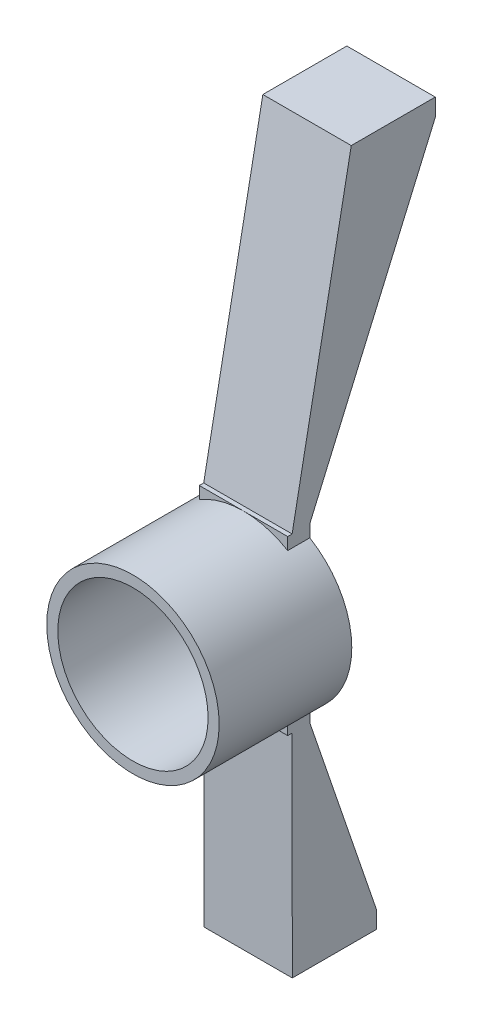
SolidWorks part; units mm, degrees
ref_plane "Front Plane" through (0, 0, 0) normal (0, 0, 1) x (1, 0, 0)
ref_plane "Top Plane" through (0, 0, 0) normal (0, 1, 0) x (1, 0, 0)
ref_plane "Right Plane" through (0, 0, 0) normal (1, 0, 0) x (0, 0, -1)
sketch "Sketch2" plane through (0, 0, 0) normal (0, 0, 1) x (1, 0, 0)
  circle A0 centre (0, 0) radius 39
  circle A1 centre (0, 0) radius 34
  dimension "D1" = 78
  dimension "D2" = 5
extrude "Boss-Extrude1" add sketch "Sketch2" along normal blind 60
ref_plane "Plane1" through (0, 0, 0) normal (1, 0, 0) x (0, 0, -1)
sketch "Sketch4" plane through (0, 0, 0) normal (1, 0, 0) x (0, 0, -1)
  line L0 (-60, 39) -> (0, 39) construction
  line L1 (0, 39) -> (0, -39) construction
  line L2 (0, -39) -> (-60, -39) construction
  line L3 (-60, -39) -> (-60, 39) construction
  line L4 (0, 39) -> (36.6421, 39) construction
  line L5 (0, 39) -> (29.2171, 190.5797) construction
  line L6 (-8, 39) -> (21.1116, 190.0326) construction
  line L7 (-8, 39) -> (18.7538, 177.8)
  line L8 (18.7538, 177.8) -> (56.7538, 177.8)
  line L9 (0, 39) -> (25.2118, 169.8)
  line L10 (25.2118, 169.8) -> (56.7538, 169.8)
  line L11 (56.7538, 169.8) -> (56.7538, 177.8)
  line L12 (0, 39) -> (-8, 39)
  point P8 (-8, 39)
  point P13 (18.7538, 177.8)
  point P14 (25.2118, 169.8)
  dimension "D1" = 8
  dimension "D2" = 79.09
  dimension "D3" = 100.91
  dimension "D4" = 138.8
  dimension "D5" = 130.8
  dimension "D6" = 38
extrude "Boss-Extrude2" add sketch "Sketch4" along normal mid plane 40 separate body
sketch "Sketch5" plane through (0, 0, 0) normal (0, 0, -1) x (-1, 0, 0)
  line L0 (-20, 39) -> (-20, 33.4813)
  line L1 (20, 39) -> (20, 33.4813)
  line L4 (20, 39) -> (20, 169.8)
  line L5 (20, 169.8) -> (-20, 169.8)
  line L6 (-20, 169.8) -> (-20, 39)
  line L7 (-20, 39) -> (20, 39)
  line L11 (-20, 39) -> (20, 39)
  circle A1 centre (0, 0) radius 39
  arc A2 (20, 33.4813) -> (-20, 33.4813) centre (0, 0) ccw
  circle M6 centre (0, 0) radius 39
  dimension "D1" = 0
  dimension "D2" = 0
extrude "Boss-Extrude3" add sketch "Sketch5" against normal blind 10 contours L11 L0 M6 | L11 L1 M6
sketch "Sketch7" plane through (0, 0, 0) normal (1, 0, 0) x (0, 0, -1)
  line L0 (-60, 39) -> (0, 39) construction
  line L1 (0, 39) -> (0, -39) construction
  line L2 (0, -39) -> (-60, -39) construction
  line L3 (-60, -39) -> (-60, 39) construction
  line L4 (0, -39) -> (0.2547, -282.2623) construction
  line L5 (-8, -39) -> (-7.7959, -272.8441) construction
  line L6 (-8, -39) -> (-7.9162, -135)
  line L7 (-7.9162, -135) -> (30.0838, -135)
  line L8 (0.0922, -127) -> (30.0922, -127)
  line L9 (0, -39) -> (0.0922, -127)
  line L10 (30.0922, -127) -> (30.0838, -135)
  line L11 (0, -39) -> (-8, -39)
  point P4 (-8, -39)
  point P12 (-7.9162, -135)
  point P13 (0.0922, -127)
  dimension "D1" = 8
  dimension "D2" = 90.06
  dimension "D3" = 90.05
  dimension "D4" = 96
  dimension "D5" = 88
  dimension "D6" = 38
  dimension "D7" = 30
extrude "Boss-Extrude4" add sketch "Sketch7" along normal mid plane 40 separate body
sketch "Sketch8" plane through (0, 0, 0) normal (0, 0, -1) x (-1, 0, 0)
  line L0 (-20, -39) -> (-20, -33.4813)
  line L1 (20, -39) -> (20, -33.4813)
  line L3 (20, 33.4813) -> (20, 39)
  line L4 (20, 39) -> (-20, 39)
  line L5 (-20, 39) -> (-20, 33.4813)
  line L10 (20, -127) -> (20, -39)
  line L11 (20, -39) -> (-20, -39)
  line L12 (-20, -39) -> (-20, -127)
  line L13 (-20, -127) -> (20, -127)
  line L15 (20, -39) -> (-20, -39)
  arc A1 (-20, 33.4813) -> (20, 33.4813) centre (0, 0) ccw
  arc A2 (-20, -33.4813) -> (20, -33.4813) centre (0, 0) ccw
  arc M9 (-20, 33.4813) -> (20, 33.4813) centre (0, 0) ccw
  dimension "D1" = 0
  dimension "D2" = 0
extrude "Boss-Extrude5" add sketch "Sketch8" against normal blind 10 contours L15 L0 M9 | L15 L1 M9
sketch "Sketch9" plane through (20, 0, 0) normal (1, 0, 0) x (0, 0, -1)
  line L0 (56.7538, 169.8) -> (0, 39)
  line L9 (0, 33.4813) -> (0, 39)
  line L10 (0, 39) -> (25.2118, 169.8)
  line L11 (25.2118, 169.8) -> (56.7538, 169.8)
  line L12 (56.7538, 169.8) -> (56.7538, 177.8)
  line L13 (56.7538, 177.8) -> (18.7538, 177.8)
  line L14 (18.7538, 177.8) -> (-8, 39)
  line L15 (-8, 39) -> (-10, 39)
  line L16 (-10, 39) -> (-10, 33.4813)
  line L17 (-10, 33.4813) -> (0, 33.4813)
  line L19 (0, 39) -> (25.2118, 169.8)
  line L20 (25.2118, 169.8) -> (56.7538, 169.8)
  dimension "D1" = 0
extrude "Boss-Extrude6" add sketch "Sketch9" against normal blind 8
sketch "Sketch10" plane through (-20, 0, 0) normal (-1, 0, 0) x (0, 0, 1)
  line L3 (0, 39) -> (-25.2118, 169.8)
  line L4 (-25.2118, 169.8) -> (-56.7538, 169.8)
  line L5 (-56.7538, 169.8) -> (0, 39)
  line L6 (0, 39) -> (-25.2118, 169.8)
  line L7 (-25.2118, 169.8) -> (-56.7538, 169.8)
  line L8 (-56.7538, 169.8) -> (0, 39)
  dimension "D1" = 0
extrude "Boss-Extrude7" add sketch "Sketch10" against normal blind 8
sketch "Sketch11" plane through (20, 0, 0) normal (1, 0, 0) x (0, 0, -1)
  line L0 (0, -39) -> (30.0922, -127)
  line L9 (0.0922, -127) -> (0, -39)
  line L10 (0, -39) -> (0, -33.4813)
  line L11 (0, -33.4813) -> (-10, -33.4813)
  line L12 (-10, -33.4813) -> (-10, -39)
  line L13 (-10, -39) -> (-8, -39)
  line L14 (-8, -39) -> (-7.9162, -135)
  line L15 (-7.9162, -135) -> (30.0838, -135)
  line L16 (30.0838, -135) -> (30.0922, -127)
  line L17 (30.0922, -127) -> (0.0922, -127)
  line L18 (0.0922, -127) -> (0, -39)
  line L26 (30.0922, -127) -> (0.0922, -127)
  dimension "D1" = 0
extrude "Boss-Extrude8" add sketch "Sketch11" against normal blind 8
sketch "Sketch12" plane through (-20, 0, 0) normal (-1, 0, 0) x (0, 0, 1)
  line L3 (-30.0922, -127) -> (-0.0922, -127)
  line L4 (-0.0922, -127) -> (0, -39)
  line L5 (0, -39) -> (-30.0922, -127)
  line L6 (-30.0922, -127) -> (-0.0922, -127)
  line L7 (-0.0922, -127) -> (0, -39)
  line L8 (0, -39) -> (-30.0922, -127)
  dimension "D1" = 0
extrude "Boss-Extrude9" add sketch "Sketch12" against normal blind 8
